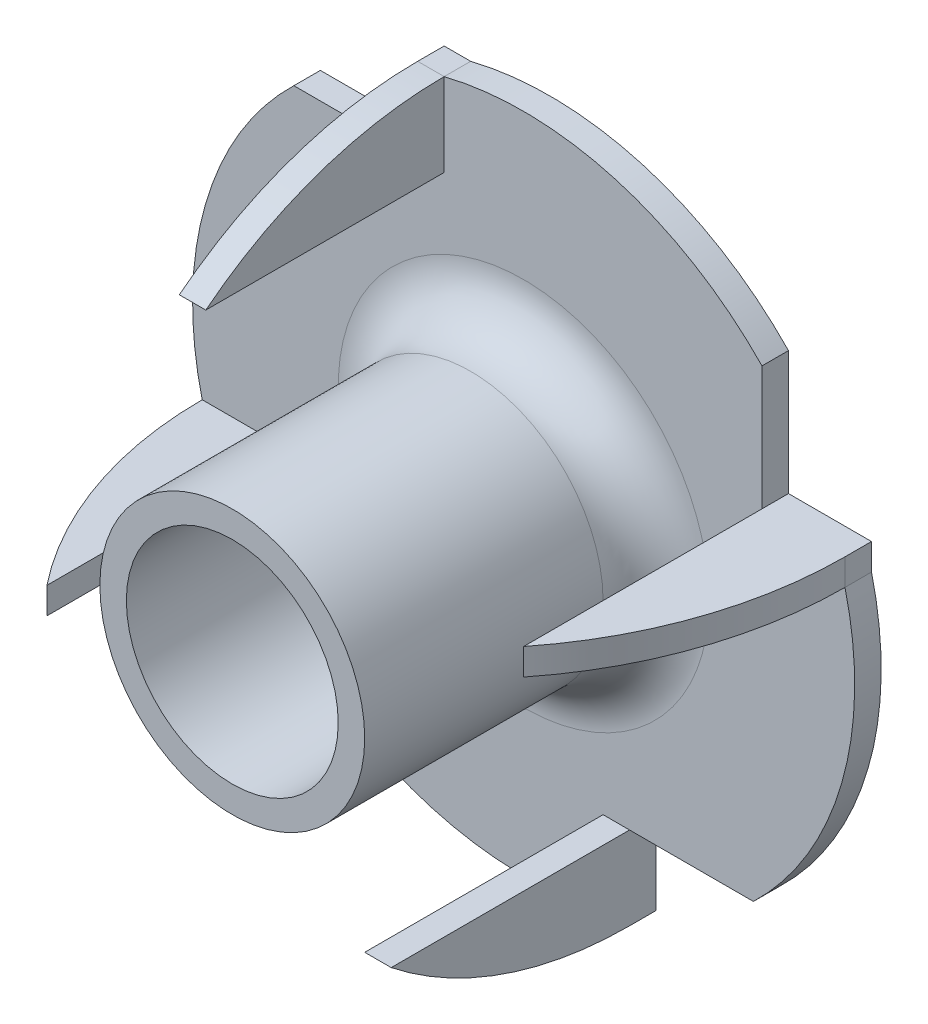
SolidWorks part; units mm, degrees
ref_plane "Front Plane" through (0, 0, 0) normal (1, 0, 0) x (0, 1, 0)
ref_plane "Top Plane" through (0, 0, 0) normal (0, 0, 1) x (0, 1, 0)
ref_plane "Right Plane" through (0, 0, 0) normal (0, 1, 0) x (-1, 0, 0)
sketch "Sketch1" plane through (0, 0, 0) normal (1, 0, 0) x (0, 1, 0)
  line L0 (5, 11) -> (5, 2)
  line L1 (7, 0) -> (12.5, 0)
  line L2 (0, 14.9922) -> (0, 10.4867) construction
  arc A0 (5, 2) -> (7, 0) centre (7, 2) ccw
  point P8 (3.7804, 12)
  dimension "D1" = 2
  dimension "D2" = 11
  dimension "D3" = 25
  dimension "D4" = 10
revolve "Revolve-Thin2" add sketch "Sketch1" angle 360 about L2
sketch "Sketch2" plane through (0, 0, 0) normal (0, 0, 1) x (0, 1, 0)
  line L1 (-8.6747, 9) -> (-3, 9)
  line L2 (-8.6747, 9) -> (-8.6747, 12.1347)
  line L3 (-8.6747, 12.1347) -> (-3, 12.1347)
  line L4 (-3, 9) -> (-3, 12.1347)
  circle A0 centre (0, 0) radius 12.5 construction
  dimension "D1" = 3
  dimension "D2" = 9
extrude "Cut-Extrude1" cut sketch "Sketch2" against normal up to next
sketch "Sketch3" plane through (0, -3, 0) normal (0, -1, 0) x (1, 0, 0)
  line L0 (-9, -1) -> (-9, 9)
  line L1 (-9, -1) -> (-12.1347, -1)
  line L2 (-12.1347, -1) -> (-12.1347, 0)
  line L3 (12.5, 0) -> (-12.5, 0) construction
  arc A1 (-12.1347, 0) -> (-9, 9) centre (2.3527, 0) cw
  dimension "D1" = 9
extrude "Boss-Extrude1" add sketch "Sketch3" along normal blind 1
pattern_circular "CirPattern1" count 4 over 360 about axis through (0, 0, 0) along (0, 0, 1) of "Cut-Extrude1", "Boss-Extrude1"
